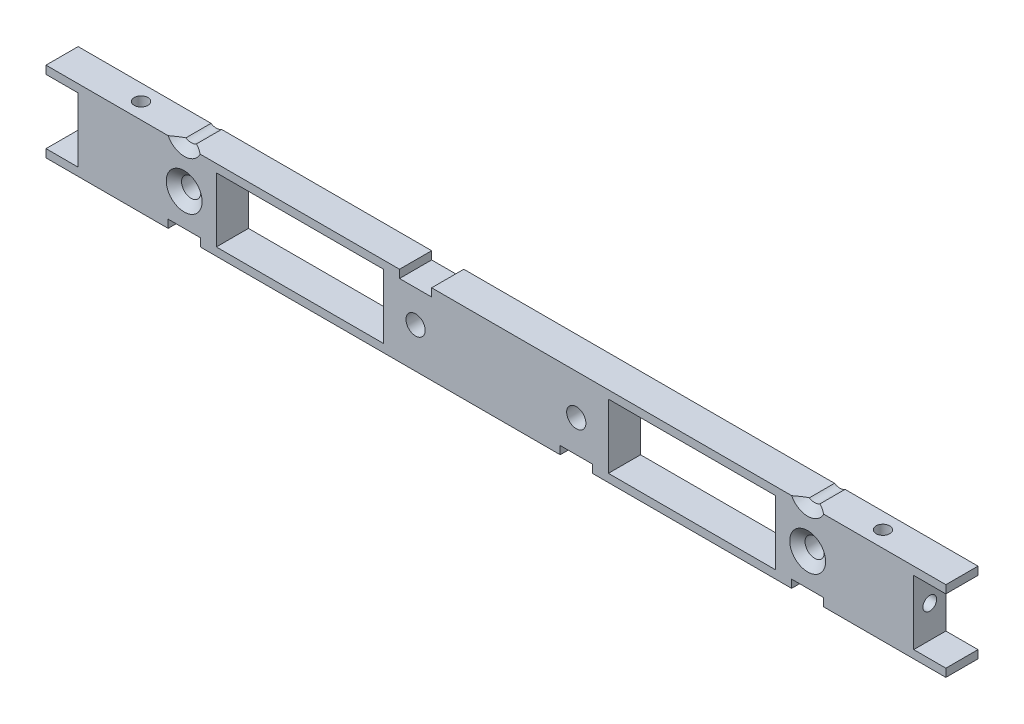
SolidWorks part; units mm, degrees
material "6061-T6 (SS)"
ref_plane "Front Plane" through (0, 0, 0) normal (0, 0, 1) x (1, 0, 0)
ref_plane "Top Plane" through (0, 0, 0) normal (0, 1, 0) x (1, 0, 0)
ref_plane "Right Plane" through (0, 0, 0) normal (1, 0, 0) x (0, 0, -1)
sketch "Sketch1" plane through (0, 0, 0) normal (0, 0, 1) x (1, 0, 0)
  line L0 (0, 3.175) -> (0, -12.7) construction
  line L1 (-88.9, 3.175) -> (88.9, 3.175)
  line L2 (-88.9, 3.175) -> (-88.9, 1.5875)
  line L3 (-88.9, -12.7) -> (88.9, -12.7)
  line L4 (88.9, 3.175) -> (88.9, 1.5875)
  line L7 (-88.9, 1.5875) -> (-82.55, 1.5875)
  line L8 (88.9, -11.1125) -> (82.55, -11.1125)
  line L9 (-88.9, -11.1125) -> (-82.55, -11.1125)
  line L10 (-82.55, 1.5875) -> (-82.55, -11.1125)
  line L11 (-88.9, -11.1125) -> (-88.9, -12.7)
  line L12 (82.55, 1.5875) -> (82.55, -11.1125)
  line L13 (88.9, 1.5875) -> (82.55, 1.5875)
  line L14 (88.9, -11.1125) -> (88.9, -12.7)
  point P0 (0, 0)
  dimension "D1" = 177.8
  dimension "D2" = 15.875
  dimension "D3" = 6.35
  dimension "D4" = 1.5875
  dimension "D5" = 1.5875
extrude "Boss-Extrude1" add sketch "Sketch1" along normal blind 6.35
ref_plane "Plane1" through (0, 0, 0) normal (1, 0, 0) x (0, 0, -1)
hole_wizard "Tap Drill for #6-32 Tap1" positions "Sketch3" profile "Sketch4" hole size "#6-32" standard "ANSI Inch"
sketch "Sketch3" plane through (-82.55, 0, 0) normal (-1, 0, 0) x (0, 0, 1)
  line L0 (6.35, 1.5875) -> (0, 1.5875) construction
  line L1 (0, 1.5875) -> (0, -11.1125) construction
  point P0 (3.175, -4.7625)
  point P2 (3.175, -4.7625)
  dimension "D1" = 6.35
  dimension "D2" = 6.35
  dimension "D3" = 3.175
  dimension "D4" = 3.175
sketch "Sketch4" plane through (-82.55, -4.7625, 3.175) normal (0, 1, 0) x (0, 0, 1)
  line L0 (0, 0) -> (0, 13.5127)
  line L1 (0, 13.5127) -> (1.3525, 12.7)
  line L2 (1.3525, 12.7) -> (1.3525, 0)
  line L5 (1.3525, 0) -> (0, 0)
  line L10 (0, 13.5127) -> (-1.3526, 12.7) construction
  line L11 (0, -6.35) -> (0, 107.95) construction
  dimension "Hole Dia." = 2.7051
  dimension "Hole Depth" = 12.7
  dimension "Drill Angle" = 118
mirror "Mirror1" about plane through (0, 0, 0) normal (1, 0, 0) of "Tap Drill for #6-32 Tap1"
hole_wizard "Tap Drill for #6-32 Tap2" positions "Sketch6" profile "Sketch5" hole size "#6-32" standard "ANSI Inch"
sketch "Sketch6" plane through (0, 3.175, 0) normal (0, 1, 0) x (1, 0, 0)
  line L0 (-88.9, -6.35) -> (-88.9, 0) construction
  point P0 (-73.2896, -3.175)
  point P9 (-88.9, -3.175)
  dimension "D1" = 15.6104
sketch "Sketch5" plane through (-73.2896, 3.175, 3.175) normal (1, 0, 0) x (0, 0, 1)
  line L0 (0, 0) -> (0, 7.1627)
  line L1 (0, 7.1627) -> (1.3525, 6.35)
  line L2 (1.3525, 6.35) -> (1.3525, 0)
  line L5 (1.3525, 0) -> (0, 0)
  line L10 (0, 7.1627) -> (-1.3526, 6.35) construction
  line L11 (0, -6.35) -> (0, 107.95) construction
  dimension "Hole Dia." = 2.7051
  dimension "Hole Depth" = 6.35
  dimension "Drill Angle" = 118
ref_plane "Plane2" through (0, -4.7625, 0) normal (0, -1, 0) x (-1, 0, 0)
mirror "Mirror2" about plane through (0, 0, 0) normal (1, 0, 0) of "Tap Drill for #6-32 Tap2"
mirror "Mirror3" about plane through (0, -4.7625, 0) normal (0, -1, 0) of "Mirror2", "Tap Drill for #6-32 Tap2"
sketch "Sketch7" plane through (0, 0, 6.35) normal (0, 0, 1) x (1, 0, 0)
  line L0 (-64.77, 11.1125) -> (-58.42, 11.1125) construction
  line L1 (-64.77, 11.1125) -> (-64.77, 12.7) construction
  line L2 (-58.42, 11.1125) -> (-58.42, 12.7) construction
  line L3 (-64.77, 12.7) -> (-58.42, 12.7) construction
  line L4 (-64.77, -11.1125) -> (-58.42, -11.1125) construction
  line L5 (-64.77, -12.7) -> (-64.77, -11.1125) construction
  line L6 (-88.9, -12.7) -> (88.9, -12.7) construction
  line L7 (-58.42, -12.7) -> (-58.42, -11.1125) construction
  line L8 (58.42, -11.1125) -> (58.42, -12.7) construction
  line L9 (64.77, -11.1125) -> (58.42, -11.1125) construction
  line L10 (64.77, -11.1125) -> (64.77, -12.7) construction
  line L11 (58.42, 12.7) -> (58.42, 11.1125) construction
  line L12 (64.77, 11.1125) -> (58.42, 11.1125) construction
  line L13 (64.77, 12.7) -> (64.77, 11.1125) construction
  line L14 (64.77, 12.7) -> (58.42, 12.7) construction
  line L15 (-64.77, 11.1125) -> (-58.42, 11.1125)
  line L16 (-64.77, 11.1125) -> (-64.77, 12.7)
  line L17 (-58.42, 11.1125) -> (-58.42, 12.7)
  line L18 (-64.77, 12.7) -> (-58.42, 12.7)
  line L19 (-64.77, -11.1125) -> (-58.42, -11.1125)
  line L20 (-64.77, -12.7) -> (-64.77, -11.1125)
  line L21 (-64.77, -12.7) -> (-58.42, -12.7)
  line L22 (-58.42, -12.7) -> (-58.42, -11.1125)
  line L23 (58.42, -11.1125) -> (58.42, -12.7)
  line L24 (64.77, -11.1125) -> (58.42, -11.1125)
  line L25 (64.77, -11.1125) -> (64.77, -12.7)
  line L26 (58.42, 12.7) -> (58.42, 11.1125)
  line L27 (64.77, 11.1125) -> (58.42, 11.1125)
  line L28 (64.77, 12.7) -> (64.77, 11.1125)
  line L29 (64.77, 12.7) -> (58.42, 12.7)
  line L30 (58.42, -12.7) -> (64.77, -12.7)
extrude "Cut-Extrude1" cut sketch "Sketch7" against normal through all
sketch "Sketch10" plane through (0, 0, 0) normal (0, 0, -1) x (-1, 0, 0)
  line L0 (-19.05, 11.1125) -> (-19.05, 12.7) construction
  line L1 (-19.05, 11.1125) -> (-12.7, 11.1125) construction
  line L2 (-12.7, 11.1125) -> (-12.7, 12.7) construction
  line L3 (12.7, 1.5875) -> (19.05, 1.5875) construction
  line L4 (19.05, 1.5875) -> (19.05, 3.175) construction
  line L5 (12.7, 1.5875) -> (12.7, 3.175) construction
  line L6 (88.9, 3.175) -> (-88.9, 3.175) construction
  line L7 (-19.05, -11.1125) -> (-12.7, -11.1125) construction
  line L8 (-19.05, -12.7) -> (-19.05, -11.1125) construction
  line L9 (-12.7, -12.7) -> (-12.7, -11.1125) construction
  line L10 (58.42, -12.7) -> (-58.42, -12.7) construction
  line L11 (19.05, -22.225) -> (19.05, -20.6375) construction
  line L12 (12.7, -20.6375) -> (19.05, -20.6375) construction
  line L13 (12.7, -22.225) -> (12.7, -20.6375) construction
  line L14 (-19.05, 11.1125) -> (-19.05, 12.7)
  line L15 (-19.05, 11.1125) -> (-12.7, 11.1125)
  line L16 (-12.7, 11.1125) -> (-12.7, 12.7)
  line L17 (12.7, 1.5875) -> (19.05, 1.5875)
  line L18 (19.05, 1.5875) -> (19.05, 3.175)
  line L19 (12.7, 1.5875) -> (12.7, 3.175)
  line L20 (19.05, 3.175) -> (12.7, 3.175)
  line L21 (-19.05, -11.1125) -> (-12.7, -11.1125)
  line L22 (-19.05, -12.7) -> (-19.05, -11.1125)
  line L23 (-12.7, -12.7) -> (-12.7, -11.1125)
  line L24 (19.05, -22.225) -> (12.7, -22.225)
  line L25 (19.05, -22.225) -> (19.05, -20.6375)
  line L26 (12.7, -20.6375) -> (19.05, -20.6375)
  line L27 (12.7, -22.225) -> (12.7, -20.6375)
  line L28 (-12.7, 12.7) -> (-19.05, 12.7)
  line L29 (-12.7, -12.7) -> (-19.05, -12.7)
  line L30 (88.9, 3.175) -> (-88.9, 3.175) construction
  line L31 (-55.245, 1.5875) -> (-22.225, 1.5875)
  line L32 (-55.245, 1.5875) -> (-55.245, -11.1125)
  line L33 (-55.245, -11.1125) -> (-22.225, -11.1125)
  line L34 (-22.225, 1.5875) -> (-22.225, -11.1125)
  line L35 (22.225, -11.1125) -> (55.245, -11.1125)
  line L36 (22.225, -11.1125) -> (22.225, 1.5875)
  line L37 (22.225, 1.5875) -> (55.245, 1.5875)
  line L38 (55.245, -11.1125) -> (55.245, 1.5875)
  line L39 (58.42, 11.1125) -> (58.42, 12.7) construction
  dimension "D1" = 1.5875
  dimension "D2" = 1.5875
  dimension "D3" = 1.5875
  dimension "D4" = 1.5875
  dimension "D5" = 3.175
  dimension "D6" = 3.175
  dimension "D7" = 3.175
  dimension "D8" = 3.175
extrude "Cut-Extrude5" cut sketch "Sketch10" against normal through all
hole_wizard "CSK for #6 Flat Head Machine Screw (100)1" positions "Sketch9" profile "Sketch8" countersink size "#6" standard "ANSI Inch" end condition through all
sketch "Sketch9" plane through (0, 0, 6.35) normal (0, 0, 1) x (1, 0, 0)
  line L0 (-64.77, 11.1125) -> (-58.42, 11.1125) construction
  line L1 (-38.735, 3.175) -> (-38.735, -12.7) construction
  line L2 (-88.9, 3.175) -> (88.9, 3.175) construction
  line L3 (-58.42, -12.7) -> (12.7, -12.7) construction
  point P0 (-61.595, 4.7625)
  point P2 (-61.595, -4.7625)
  point P7 (-61.595, 11.1125)
  dimension "D1" = 7.9375
  dimension "D2" = 7.9375
sketch "Sketch8" plane through (-61.595, 4.7625, 6.35) normal (1, 0, 0) x (0, -1, 0)
  line L0 (0, 0) -> (0, 6.35)
  line L1 (0, 6.35) -> (1.8986, 6.35)
  line L2 (1.8986, 6.35) -> (1.8986, 1.38)
  line L3 (1.8986, 1.38) -> (3.5433, 0)
  line L5 (3.5433, 0) -> (0, 0)
  line L6 (-1.8986, 1.38) -> (-3.5433, 0) construction
  line L11 (0, -6.35) -> (0, 107.95) construction
  dimension "Thru Hole Dia." = 3.7973
  dimension "Thru Hole Depth" = 6.35
  dimension "Near C'Sink Dia." = 7.0866
  dimension "Near C'Sink Angle" = 100
hole_wizard "CSK for #6 Flat Head Machine Screw (100)2" positions "Sketch12" profile "Sketch11" countersink size "#6" standard "ANSI Inch" end condition through all
sketch "Sketch12" plane through (0, 0, 0) normal (0, 0, -1) x (-1, 0, 0)
  line L0 (12.7, 1.5875) -> (19.05, 1.5875) construction
  line L1 (12.7, 3.175) -> (-88.9, 3.175) construction
  line L2 (58.42, -12.7) -> (-12.7, -12.7) construction
  point P0 (15.875, -4.7625)
  point P2 (15.875, -4.7625)
  point P7 (15.875, 1.5875)
  dimension "D1" = 7.9375
  dimension "D2" = 7.9375
sketch "Sketch11" plane through (-15.875, -4.7625, 0) normal (1, 0, 0) x (0, 1, 0)
  line L0 (0, 0) -> (0, 6.35)
  line L1 (0, 6.35) -> (1.8986, 6.35)
  line L2 (1.8986, 6.35) -> (1.8986, 1.38)
  line L3 (1.8986, 1.38) -> (3.5433, 0)
  line L5 (3.5433, 0) -> (0, 0)
  line L6 (-1.8986, 1.38) -> (-3.5433, 0) construction
  line L11 (0, -6.35) -> (0, 107.95) construction
  dimension "Thru Hole Dia." = 3.7973
  dimension "Thru Hole Depth" = 6.35
  dimension "Near C'Sink Dia." = 7.0866
  dimension "Near C'Sink Angle" = 100
mirror "Mirror5" about plane through (0, 0, 0) normal (1, 0, 0) of "CSK for #6 Flat Head Machine Screw (100)1", "CSK for #6 Flat Head Machine Screw (100)2"
